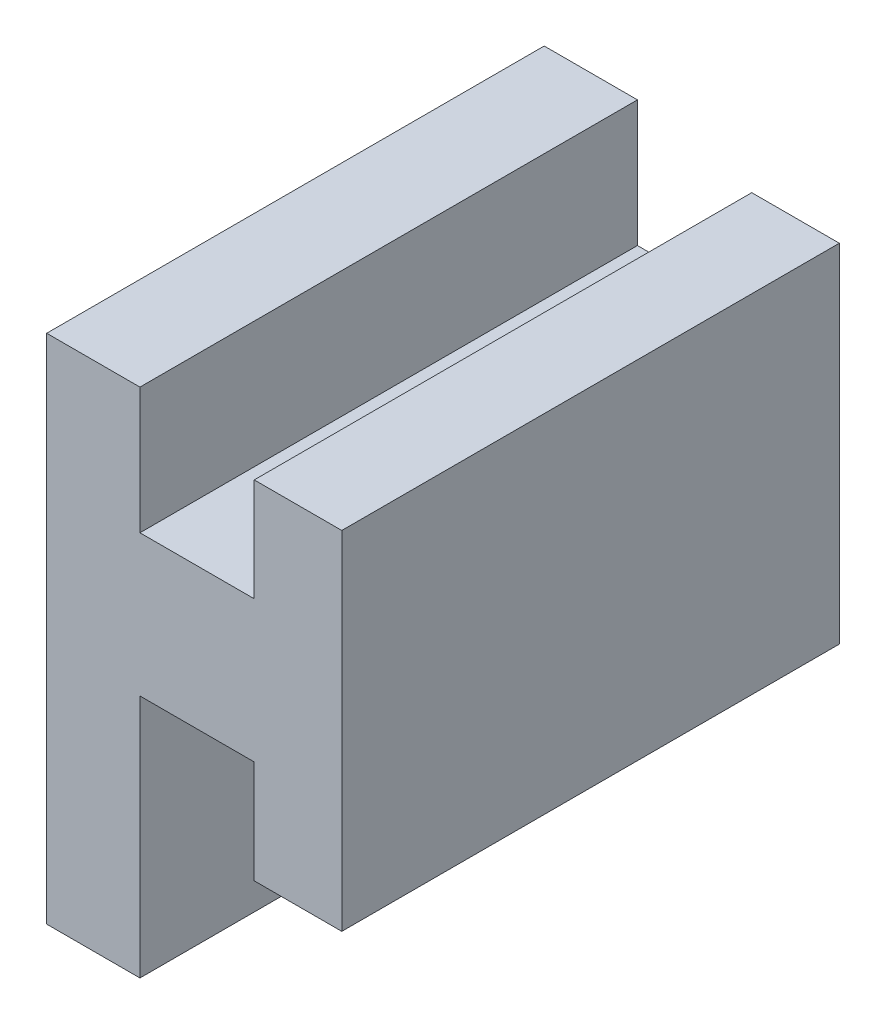
SolidWorks part; units mm, degrees
ref_plane "Front Plane" through (0, 0, 0) normal (0, 0, 1) x (1, 0, 0)
ref_plane "Top Plane" through (0, 0, 0) normal (0, 1, 0) x (1, 0, 0)
ref_plane "Right Plane" through (0, 0, 0) normal (1, 0, 0) x (0, 0, -1)
sketch "Sketch2" plane through (0, 0, 0) normal (0, 0, 1) x (1, 0, 0)
  line L0 (-32, -20.059) -> (-34.1144, -20.059) construction
  line L1 (-34.1144, -20.059) -> (-34.1144, -9.533) construction
  line L2 (-34.1144, -9.533) -> (-32, -9.533) construction
  line L3 (-32, -8.1732) -> (-32, -12.0692) construction
  line L4 (-32, -9.533) -> (-32, -12.0692) construction
  line L5 (-32, -12.0692) -> (-29.9428, -12.0692) construction
  line L6 (-29.9428, -12.0692) -> (-29.9428, -10) construction
  line L7 (-29.9428, -12.0692) -> (-29.9428, -10) construction
  line L8 (-29.9428, -10) -> (-27.9428, -10) construction
  line L9 (-27.9428, -10) -> (-27.9428, -17.2189) construction
  line L10 (-27.9428, -17.2189) -> (-29.9428, -17.2189) construction
  line L11 (-29.9428, -17.2189) -> (-29.9428, -15.1497) construction
  line L12 (-29.9428, -15.1497) -> (-32, -15.1497) construction
  line L13 (-32, -15.1497) -> (-32, -20.059) construction
  line L14 (-29.9428, -15.1497) -> (-32, -15.1497) construction
  line L15 (-32, -15.1497) -> (-32, -20.059) construction
  line L16 (-32.12, -9.653) -> (-32.12, -12.1892)
  line L17 (-32.12, -12.1892) -> (-29.8228, -12.1892)
  line L18 (-29.8228, -12.1892) -> (-29.8228, -10.12)
  line L19 (-29.8228, -10.12) -> (-28.0628, -10.12)
  line L20 (-28.0628, -10.12) -> (-28.0628, -17.0989)
  line L21 (-28.0628, -17.0989) -> (-29.8228, -17.0989)
  line L22 (-29.8228, -17.0989) -> (-29.8228, -15.0297)
  line L23 (-29.8228, -15.0297) -> (-32.12, -15.0297)
  line L24 (-32.12, -15.0297) -> (-32.12, -19.939)
  line L25 (-32.12, -19.939) -> (-33.9944, -19.939)
  line L26 (-33.9944, -19.939) -> (-33.9944, -9.653)
  line L27 (-33.9944, -9.653) -> (-32.12, -9.653)
  dimension "D1" = 0.12
extrude "Boss-Extrude1" add sketch "Sketch2" against normal blind 10
